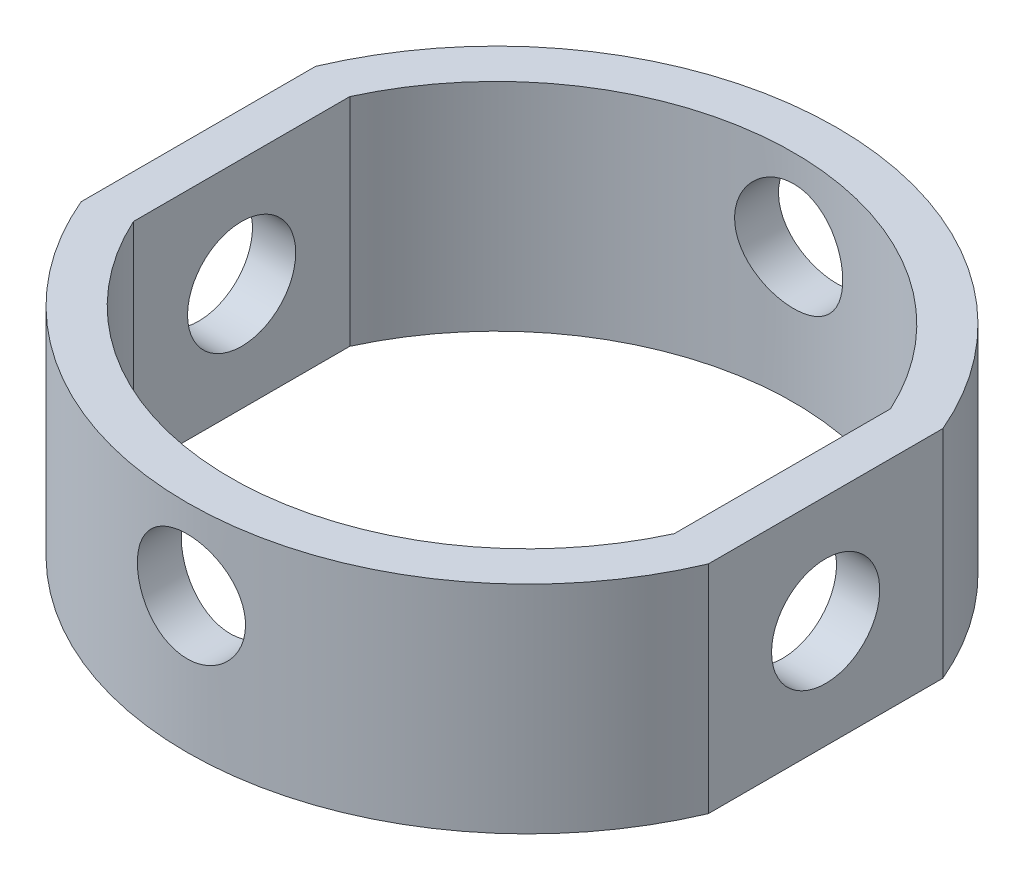
SolidWorks part; units mm, degrees
ref_plane "Front Plane" through (0, 0, 0) normal (0, 0, 1) x (1, 0, 0)
ref_plane "Top Plane" through (0, 0, 0) normal (0, 1, 0) x (1, 0, 0)
ref_plane "Right Plane" through (0, 0, 0) normal (1, 0, 0) x (0, 0, -1)
sketch "Sketch1" plane through (0, 0, 0) normal (0, 1, 0) x (1, 0, 0)
  line L0 (0, 0) -> (-25904.0422, 0) construction
  line L1 (0, 0) -> (0, -25904.0422) construction
  line L2 (-25, 10) -> (-25, -10)
  line L3 (25, 10) -> (25, -10)
  line L4 (29, 10.8424) -> (29, -10.8424)
  line L5 (-29, 10.8424) -> (-29, -10.8424)
  arc A0 (-25, 10) -> (25, 10) centre (0, -1.4638) cw
  arc A1 (-25, -10) -> (25, -10) centre (0, 1.4638) ccw
  arc A2 (-29, 10.8424) -> (29, 10.8424) centre (0, -1.4638) cw
  arc A3 (-29, -10.8424) -> (29, -10.8424) centre (0, 1.4638) ccw
  point P5 (25, 0)
  point P6 (-25, 0)
  point P10 (-25, 0)
  dimension "D4" = 27.5031
  dimension "D1" = 25
  dimension "D2" = 25
  dimension "D3" = 20
  dimension "D5" = 4
extrude "Boss-Extrude1" add sketch "Sketch1" along normal mid plane 20
sketch "Sketch2" plane through (-29, 0, 0) normal (-1, 0, 0) x (0, 0, 1)
  circle A0 centre (0, 0) radius 5
extrude "Cut-Extrude1" cut sketch "Sketch2" against normal up to surface (58 mm away) up to face at (29, 0, 0)
ref_plane "Plane1" through (0, 0, 30.0393) normal (0, 0, 1) x (1, 0, 0)
sketch "Sketch3" plane through (0, 0, 30.0393) normal (0, 0, 1) x (1, 0, 0)
  line L0 (-29, -10) -> (29, -10) construction
  line L1 (0, 0) -> (0, -50000) construction
  circle A0 centre (0, 2.5) radius 5
  dimension "D1" = 10
  dimension "D2" = 12.5
extrude "Cut-Extrude2" cut sketch "Sketch3" against normal up to surface (59.6792 mm away)
equation "\"D2@Sketch1\"=\"D1@Sketch1\""
